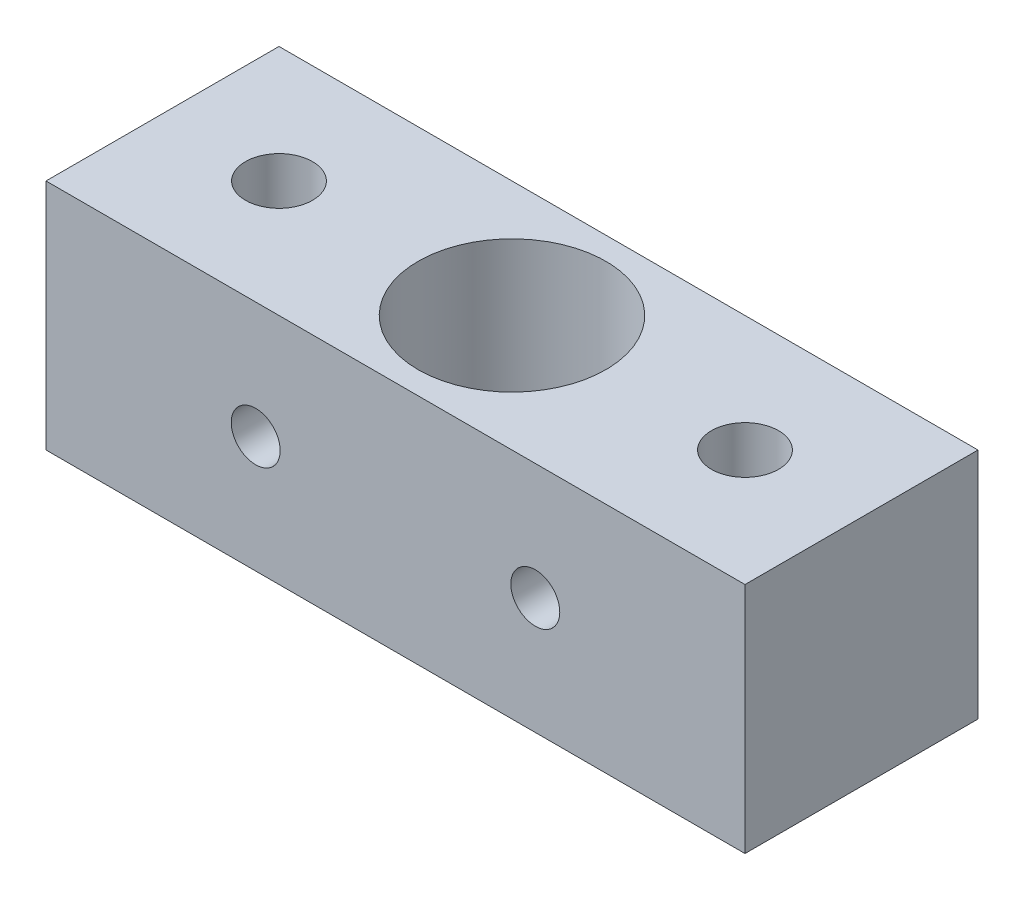
SolidWorks part; units mm, degrees
material "ABS"
ref_plane "Front Plane" through (0, 0, 0) normal (0, 0, 1) x (1, 0, 0)
ref_plane "Top Plane" through (0, 0, 0) normal (0, 1, 0) x (1, 0, 0)
ref_plane "Right Plane" through (0, 0, 0) normal (1, 0, 0) x (0, 0, -1)
sketch "Sketch1" plane through (0, 0, 0) normal (0, 1, 0) x (1, 0, 0)
  line L1 (-19.05, 6.35) -> (19.05, 6.35)
  line L2 (-19.05, 6.35) -> (-19.05, -6.35)
  line L3 (-19.05, -6.35) -> (19.05, -6.35)
  line L4 (19.05, 6.35) -> (19.05, -6.35)
  line L5 (-19.05, 6.35) -> (19.05, -6.35) construction
  line L6 (-19.05, -6.35) -> (19.05, 6.35) construction
  point P0 (0, 0)
  dimension "D1" = 38.1
  dimension "D2" = 12.7
extrude "Boss-Extrude1" add sketch "Sketch1" along normal blind 12.7
sketch "Sketch2" plane through (0, 12.7, 0) normal (0, 1, 0) x (1, 0, 0)
  circle A0 centre (0, 0) radius 5.1181
  circle A1 centre (-12.7, 0) radius 1.8288
  circle A2 centre (12.7, 0) radius 1.8288
  dimension "D1" = 3.6576
  dimension "D2" = 3.6576
  dimension "D3" = 10.2362
  dimension "D4" = 12.7
  dimension "D5" = 12.7
extrude "Cut-Extrude1" cut sketch "Sketch2" against normal blind 12.7 contours A2 | A0 | A1
sketch "Sketch3" plane through (0, 0, 6.35) normal (0, 0, 1) x (1, 0, 0)
  line L0 (-19.05, 12.7) -> (19.05, 12.7) construction
  line L1 (-19.05, 0) -> (19.05, 0) construction
  circle A0 centre (-7.62, 6.35) radius 1.3335
  circle A1 centre (7.62, 6.35) radius 1.3335
  point P8 (0, 0)
  dimension "D1" = 2.667
  dimension "D2" = 2.667
  dimension "D3" = 6.35
  dimension "D4" = 7.62
  dimension "D5" = 7.62
  dimension "D6" = 6.35
extrude "Cut-Extrude2" cut sketch "Sketch3" against normal blind 12.7 contours A1 | A0
